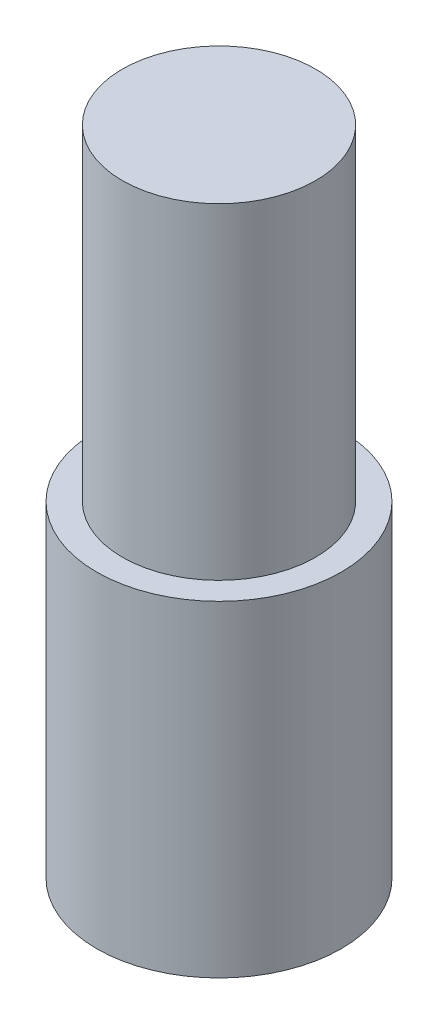
SolidWorks part; units mm, degrees
material "PUR"
ref_plane "Z" through (0, 0, 0) normal (0, 0, 1) x (1, 0, 0)
ref_plane "Y" through (0, 0, 0) normal (0, 1, 0) x (1, 0, 0)
ref_plane "X" through (0, 0, 0) normal (1, 0, 0) x (0, 0, -1)
sketch "Sketch1" plane through (0, 0, 0) normal (0, 1, 0) x (1, 0, 0)
  circle A0 centre (0, 0) radius 4.7625
  dimension "D1" = 9.525
extrude "Boss-Extrude1" add sketch "Sketch1" along normal blind 25.4
sketch "Sketch2" plane through (0, 25.4, 0) normal (0, 1, 0) x (1, 0, 0)
  circle A1 centre (0, 0) radius 5.7262
  circle A2 centre (0, 0) radius 3.7625
  circle A3 centre (0, 0) radius 3.7625
  dimension "D1" = 1
extrude "Cut-Extrude1" cut sketch "Sketch2" against normal blind 12.7
